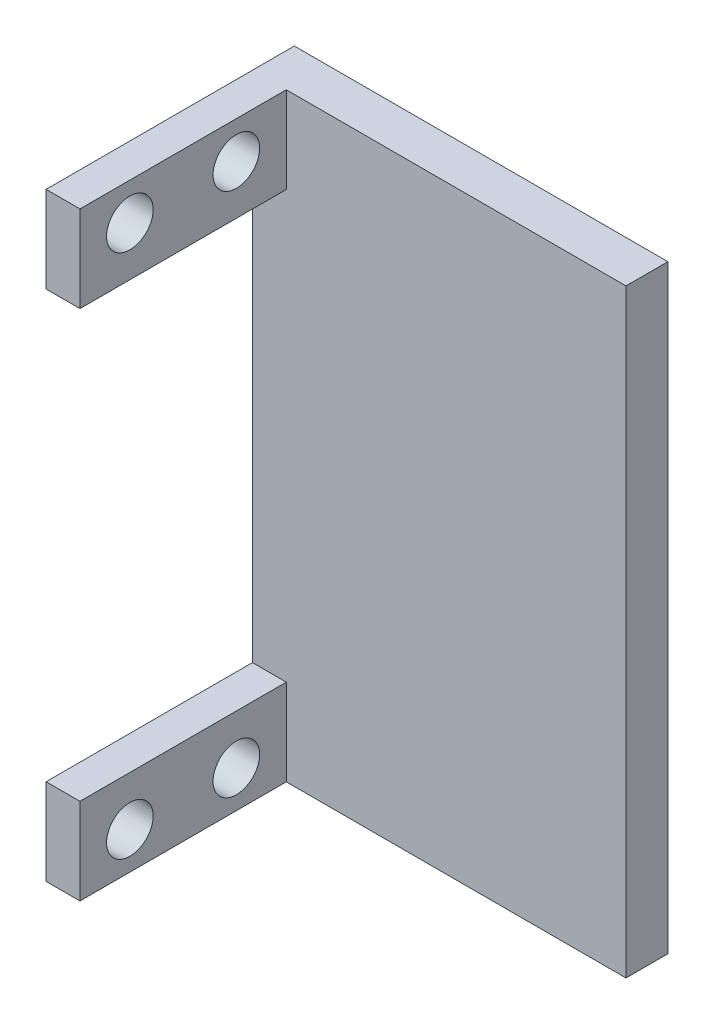
SolidWorks part; units mm, degrees
ref_plane "Front Plane" through (0, 0, 0) normal (0, 0, 1) x (1, 0, 0)
ref_plane "Top Plane" through (0, 0, 0) normal (0, 1, 0) x (1, 0, 0)
ref_plane "Right Plane" through (0, 0, 0) normal (1, 0, 0) x (0, 0, -1)
sketch "Sketch1" plane through (0, 0, 0) normal (0, 0, 1) x (1, 0, 0)
  line L12 (-10.8887, 28.6372) -> (-8.5757, 28.6372) construction
  line L13 (-15.3067, 28.6372) -> (20.3293, 28.6372)
  line L14 (-15.3067, 28.6372) -> (-15.3067, -26.5408)
  line L15 (-15.3067, -26.5408) -> (20.3293, -26.5408)
  line L16 (20.3293, 28.6372) -> (20.3293, -26.5408)
  line L17 (-10.8887, -26.5408) -> (-8.5757, -26.5408) construction
  line L18 (20.3293, 18.0631) -> (20.3293, -16.2096) construction
  point P11 (0, 0)
extrude "Boss-Extrude1" add sketch "Sketch1" along normal mid plane 4
sketch "Sketch2" plane through (0, 0, 2) normal (0, 0, 1) x (1, 0, 0)
  line L0 (-11.8739, 21.3982) -> (-12.0758, 21.3982) construction
  line L1 (-15.3067, 28.6372) -> (-12.0758, 28.6372)
  line L2 (-15.3067, 28.6372) -> (-15.3067, 21.3982)
  line L3 (-15.3067, 21.3982) -> (-12.0758, 21.3982)
  line L4 (-12.0758, 28.6372) -> (-12.0758, 21.3982)
  line L5 (-14.9257, 21.3982) -> (-11.0887, 21.3982) construction
  line L6 (-12.0758, -19.3018) -> (-11.8739, -19.3018) construction
  line L7 (-15.3067, -26.5408) -> (-12.0758, -26.5408)
  line L8 (-15.3067, -26.5408) -> (-15.3067, -19.3018)
  line L9 (-15.3067, -19.3018) -> (-12.0758, -19.3018)
  line L10 (-12.0758, -26.5408) -> (-12.0758, -19.3018)
extrude "Boss-Extrude2" add sketch "Sketch2" along normal up to surface (19.685 mm away)
sketch "Sketch3" plane through (-15.3067, 0, 0) normal (-1, 0, 0) x (0, 0, 1)
  circle A1 centre (16.9225, 26.0972) radius 2.2225
  circle A2 centre (16.9225, -24.0008) radius 2.2225
  circle A3 centre (6.7625, 26.0972) radius 2.2225
  circle A4 centre (6.7625, -24.0008) radius 2.2225
extrude "Cut-Extrude1" cut sketch "Sketch3" against normal through all
sketch "Sketch5" plane through (0, -26.5408, 0) normal (0, -1, 0) x (1, 0, 0)
  line L6 (-15.3067, -2) -> (20.3293, -2)
  line L7 (20.3293, -2) -> (20.3293, 2)
  line L8 (20.3293, 2) -> (-12.0758, 2)
  line L9 (-12.0758, 2) -> (-12.0758, 21.685)
  line L10 (-12.0758, 21.685) -> (-15.3067, 21.685)
  line L11 (-15.3067, 21.685) -> (-15.3067, -2)
  line L12 (-15.3067, -2) -> (20.3293, -2)
  line L13 (20.3293, -2) -> (20.3293, 2)
  line L14 (20.3293, 2) -> (-12.0758, 2)
  line L15 (-12.0758, 2) -> (-12.0758, 21.685)
  line L16 (-12.0758, 21.685) -> (-15.3067, 21.685)
  line L17 (-15.3067, 21.685) -> (-15.3067, -2)
  dimension "D1" = 0
extrude "Boss-Extrude4" add sketch "Sketch5" along normal blind 1
sketch "Sketch6" plane through (0, 28.6372, 0) normal (0, 1, 0) x (1, 0, 0)
  line L6 (20.3293, 2) -> (-15.3067, 2)
  line L7 (-15.3067, 2) -> (-15.3067, -21.685)
  line L8 (-15.3067, -21.685) -> (-12.0758, -21.685)
  line L9 (-12.0758, -21.685) -> (-12.0758, -2)
  line L10 (-12.0758, -2) -> (20.3293, -2)
  line L11 (20.3293, -2) -> (20.3293, 2)
  line L12 (20.3293, 2) -> (-15.3067, 2)
  line L13 (-15.3067, 2) -> (-15.3067, -21.685)
  line L14 (-15.3067, -21.685) -> (-12.0758, -21.685)
  line L15 (-12.0758, -21.685) -> (-12.0758, -2)
  line L16 (-12.0758, -2) -> (20.3293, -2)
  line L17 (20.3293, -2) -> (20.3293, 2)
  dimension "D1" = 0
extrude "Boss-Extrude5" add sketch "Sketch6" along normal blind 1
